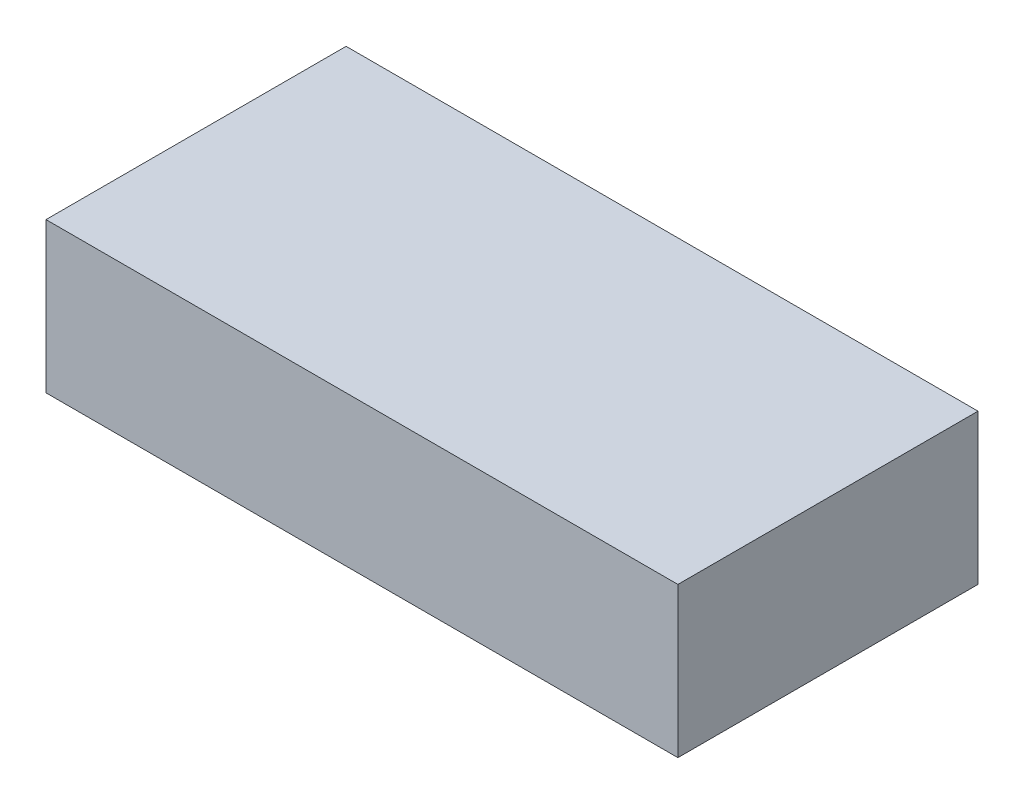
SolidWorks part; units mm, degrees
ref_plane "Front Plane" through (0, 0, 0) normal (0, 0, 1) x (1, 0, 0)
ref_plane "Top Plane" through (0, 0, 0) normal (0, 1, 0) x (1, 0, 0)
ref_plane "Right Plane" through (0, 0, 0) normal (1, 0, 0) x (0, 0, -1)
sketch "Sketch1" plane through (0, 0, 0) normal (0, 1, 0) x (1, 0, 0)
  line L1 (-37.973, -18.034) -> (37.973, -18.034)
  line L2 (-37.973, -18.034) -> (-37.973, 18.034)
  line L3 (-37.973, 18.034) -> (37.973, 18.034)
  line L4 (37.973, -18.034) -> (37.973, 18.034)
  line L5 (-37.973, -18.034) -> (37.973, 18.034) construction
  line L6 (-37.973, 18.034) -> (37.973, -18.034) construction
  point P0 (0, 0)
  dimension "D1" = 75.946
  dimension "D2" = 36.068
extrude "Boss-Extrude1" add sketch "Sketch1" along normal blind 18.034
sketch "Sketch2" plane through (-37.973, 0, 0) normal (-1, 0, 0) x (0, 0, 1)
  line L0 (0, -9.9187) -> (0, 9.9187) construction
  line L2 (-18.034, 18.034) -> (18.034, 18.034) construction
  circle A0 centre (-3.556, 8.509) radius 2.54
  circle A1 centre (3.556, 8.509) radius 2.54
  point P6 (-5.4229, 18.034)
  dimension "D1" = 5.08
  dimension "D2" = 3.556
  dimension "D3" = 9.525
extrude "Boss-Extrude2" add sketch "Sketch2" along normal blind 2.54
sketch "Sketch3" plane through (-40.513, 0, 0) normal (-1, 0, 0) x (0, 0, 1)
  line L0 (-3.556, 8.509) -> (-18.034, 8.509)
  line L1 (-18.034, 18.034) -> (-18.034, 0) construction
  line L2 (-3.556, 8.509) -> (3.556, 8.509)
  line L3 (3.556, 8.509) -> (18.034, 8.509)
  line L4 (18.034, 18.034) -> (18.034, 0) construction
  point P0 (3.556, 8.509)
  point P1 (-3.556, 8.509)
  point P3 (0, 0)
ref_plane "Plane1" through (-44.323, 0, 0) normal (-1, 0, 0) x (0, 0, 1)
sketch "Sketch4" plane through (-44.323, 0, 0) normal (-1, 0, 0) x (0, 0, 1)
  point P0 (-3.556, 8.509)
  point P1 (3.556, 8.509)
